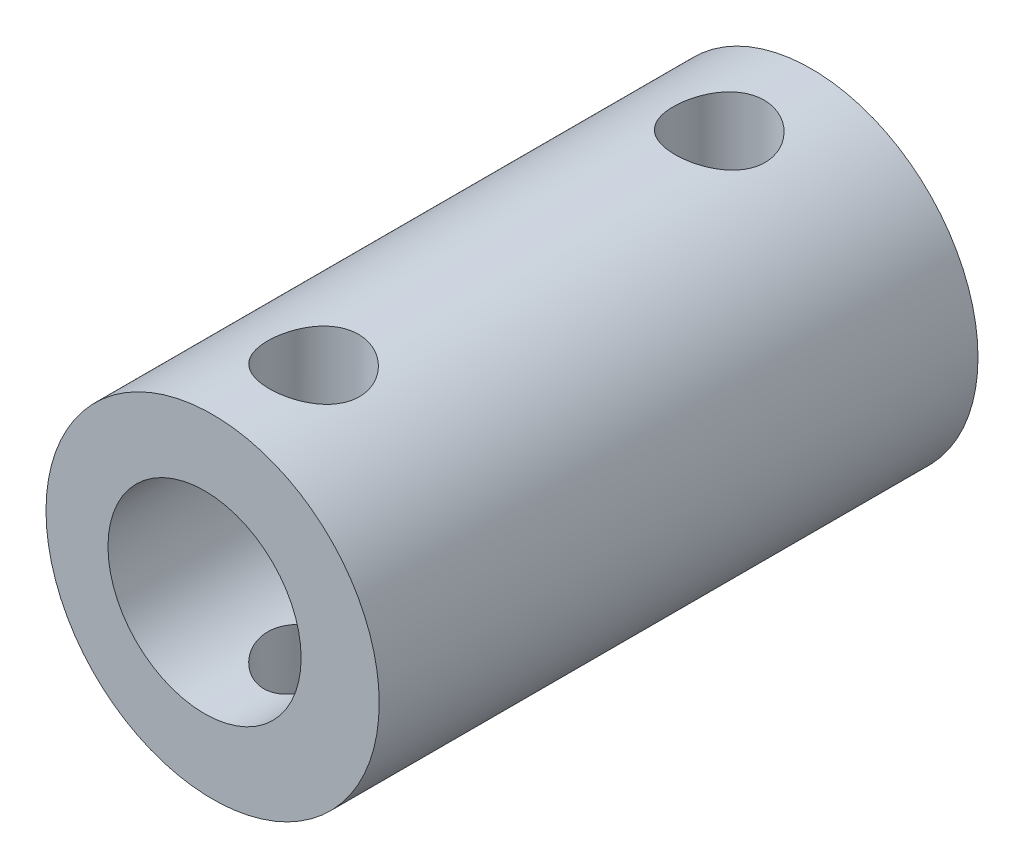
SolidWorks part; units mm, degrees
ref_plane "Front Plane" through (0, 0, 0) normal (0, 0, 1) x (1, 0, 0)
ref_plane "Top Plane" through (0, 0, 0) normal (0, 1, 0) x (1, 0, 0)
ref_plane "Right Plane" through (0, 0, 0) normal (1, 0, 0) x (0, 0, -1)
sketch "Sketch1" plane through (0, 0, 0) normal (0, 0, 1) x (1, 0, 0)
  circle A0 centre (0.3336, 0) radius 6.9
  dimension "D1" = 13.8
extrude "Boss-Extrude1" add sketch "Sketch1" along normal blind 24.8
ref_plane "Plane1" through (0, 6.9, 0) normal (0, 1, 0) x (1, 0, 0)
sketch "Sketch2" plane through (0, 6.9, 0) normal (0, 1, 0) x (1, 0, 0)
  line L0 (-6.5664, -24.8) -> (7.2336, -24.8) construction
  line L1 (7.2336, 0) -> (-6.5664, 0) construction
  circle A0 centre (0.5154, -4) radius 1.9
  circle A1 centre (0.5154, -20.8) radius 1.9
  dimension "D1" = 3.8
  dimension "D2" = 3.8
  dimension "D3" = 4
  dimension "D4" = 4
extrude "Cut-Extrude1" cut sketch "Sketch2" against normal blind 24.8
sketch "Sketch3" plane through (0, 0, 24.8) normal (0, 0, 1) x (1, 0, 0)
  circle A0 centre (0, 0) radius 4
  dimension "D1" = 8
extrude "Cut-Extrude2" cut sketch "Sketch3" against normal blind 10
sketch "Sketch4" plane through (0, 0, 0) normal (0, 0, -1) x (-1, 0, 0)
  circle A0 centre (0, 0) radius 2
  dimension "D1" = 4
extrude "Cut-Extrude3" cut sketch "Sketch4" against normal blind 10
